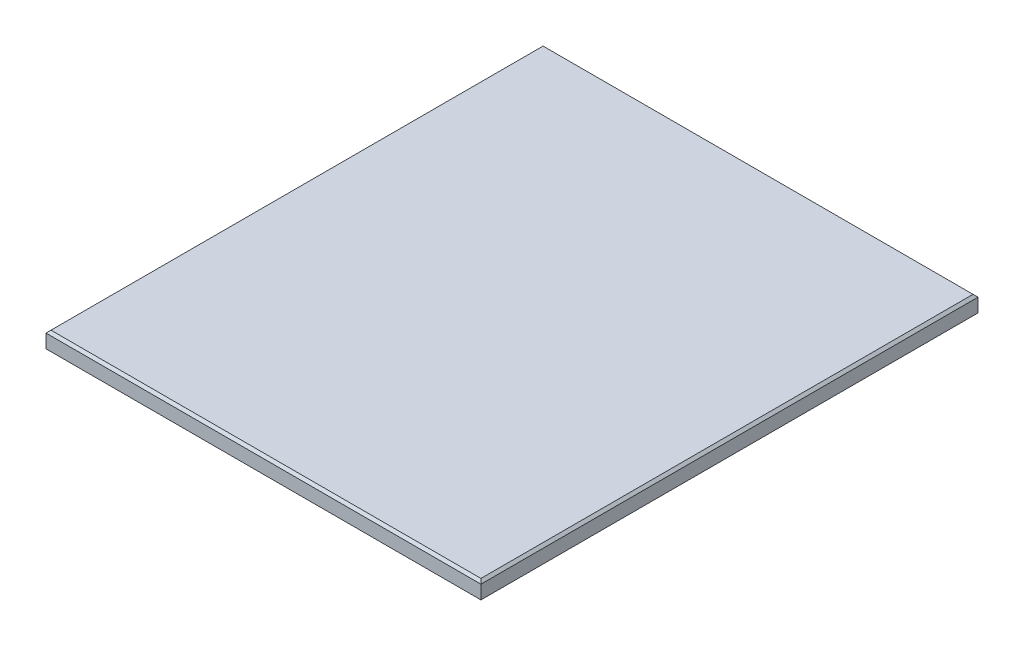
SolidWorks part; units mm, degrees
ref_plane "Front Plane" through (0, 0, 0) normal (0, 0, 1) x (1, 0, 0)
ref_plane "Top Plane" through (0, 0, 0) normal (0, 1, 0) x (1, 0, 0)
ref_plane "Right Plane" through (0, 0, 0) normal (1, 0, 0) x (0, 0, -1)
sketch "Sketch1" plane through (0, 0, 0) normal (0, 1, 0) x (1, 0, 0)
  line L1 (0, 0) -> (350, 0)
  line L2 (0, 0) -> (0, -400)
  line L3 (0, -400) -> (350, -400)
  line L4 (350, 0) -> (350, -400)
  dimension "D1" = 350
  dimension "D2" = 400
extrude "Boss-Extrude1" add sketch "Sketch1" along normal blind 15
chamfer "Chamfer1" distance 2 angle 45 8 edges at (175, 0, 400) (350, 0, 200) (175, 0, 0) (0, 0, 200) (175, 15, 0) (350, 15, 200) (175, 15, 400) (0, 15, 200)
